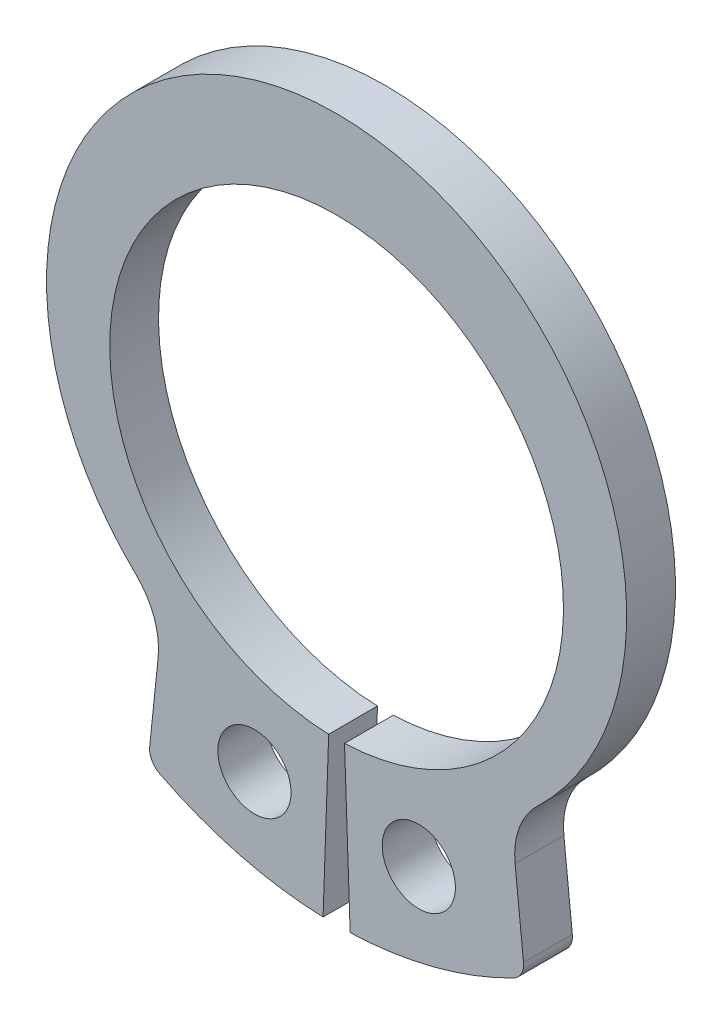
SolidWorks part; units mm, degrees
ref_plane "Front" through (0, 0, 0) normal (0, 0, 1) x (1, 0, 0)
ref_plane "Top" through (0, 0, 0) normal (0, 1, 0) x (1, 0, 0)
ref_plane "Right" through (0, 0, 0) normal (1, 0, 0) x (0, 0, -1)
sketch "Sketch1" plane through (0, 0, 0) normal (0, 0, 1) x (1, 0, 0)
  line L0 (0, 0) -> (-4.027, -2.325) construction
  line L1 (0, 7.95) -> (0, -7.95) construction
  line L2 (-3.8578, -6.9568) -> (-3.5759, -4.2445) construction
  line L4 (-3.5759, -4.2445) -> (-4.1558, -4.9328) construction
  line L5 (-3.5759, -4.2445) -> (0, 0) construction
  line L6 (0, 4.65) -> (0, 6.45) construction
  line L7 (0, 6.45) -> (0, 5.55) construction
  line L8 (0, -4.65) -> (0, -7.95) construction
  line L9 (-2.1265, -7.6653) -> (0, 0) construction
  line L10 (0, 0) -> (-0.2776, -7.95) construction
  line L11 (-3.8578, -6.9568) -> (0, 0) construction
  line L12 (-3.6489, -4.9471) -> (-4.114, -3.7868) construction
  line L13 (-3.8814, -4.3669) -> (-3.5759, -4.2445) construction
  line L14 (-1.243, -4.4808) -> (-2.1265, -7.6653) construction
  line L15 (-1.6848, -6.0731) -> (-0.9621, -6.2736) construction
  arc A0 (0, 6.45) -> (-3.5759, -4.2445) centre (0, 0.5049) ccw construction
  circle A2 centre (0, 0) radius 6.45 construction
  arc A3 (-3.8578, -6.9568) -> (-0.2776, -7.95) centre (0, 0) ccw construction
  circle A4 centre (0, 0) radius 4.65 construction
  circle A6 centre (-1.6848, -6.0731) radius 0.75 construction
  arc A7 (-4.114, -3.7868) -> (-3.6489, -4.9471) centre (-5.1622, -4.8803) cw construction
  point P5 (-4.027, -2.325)
  point P24 (-3.128, -5.6408)
  point P35 (0, 6.45)
  point P36 (0, 4.65)
  point P37 (0, -4.65)
  point P38 (0, -7.95)
  dimension "Ring ID" = 9.3
  dimension "Hole Diameter" = 1.5
  dimension "D10" = 1.5147
  dimension "Max Sec." = 1.8
  dimension "Lug Height" = 3.3
  dimension "D6" = 2
  dimension "D5" = 2.727
  dimension "D8" = 1.25
  dimension "D3" = 120
  dimension "D2" = 3.75
  dimension "D4" = 1.25
sketch "Sketch2" plane through (0, 0, 0) normal (0, 1, 0) x (1, 0, 0)
  line L0 (-6.45, 0.5) -> (-6.45, -0.5) construction
  line L2 (0, 0.5) -> (0, -0.5) construction
  line L4 (-6.45, 0) -> (6.45, 0) construction
  point P3 (-6.45, 0)
  point P6 (0, 0)
  dimension "Ring Thickness" = 1
sketch "Sketch4" plane through (0, 0, 0) normal (0, 0, 1) x (1, 0, 0)
  line L0 (-3.8578, -6.9568) -> (-3.5759, -4.2445) construction
  line L1 (-3.8578, -6.9568) -> (-3.5759, -4.2445)
  line L2 (0, 6.45) -> (0, 4.65)
  line L3 (-0.2776, -7.95) -> (-0.1623, -4.6472)
  line L4 (0, 0) -> (-0.2776, -7.95) construction
  arc A0 (0, 6.45) -> (-3.5759, -4.2445) centre (0, 0.5049) ccw construction
  arc A1 (-3.8578, -6.9568) -> (-0.2776, -7.95) centre (0, 0) ccw construction
  circle A2 centre (-1.6848, -6.0731) radius 0.75 construction
  arc A4 (0, 6.45) -> (-3.5759, -4.2445) centre (0, 0.5049) ccw
  arc A5 (-3.8578, -6.9568) -> (-0.2776, -7.95) centre (0, 0) ccw
  circle A6 centre (-1.6848, -6.0731) radius 0.75
  circle A7 centre (0, 0) radius 4.65 construction
  arc A8 (0, 4.65) -> (-0.1623, -4.6472) centre (0, 0) ccw
extrude "Boss-Extrude1" add sketch "Sketch4" along normal mid plane 1
fillet "Fillet1" radius 1.5147 1 edges at (-3.5759, -4.2445, 0)
fillet "Fillet2" radius 0.3787 1 edges at (-3.8578, -6.9568, 0)
mirror "Mirror1" about plane through (0, 6.45, 0.5) normal (-1, 0, 0) of bodies 109
sketch "Sketch3" plane through (0, 0, 0.5) normal (0, 0, 1) x (1, 0, 0)
  line L0 (3.4625, -3.1038) -> (4.1159, -3.7849) construction
  line L1 (4.1159, -3.7849) -> (4.797, -3.1315) construction
  line L2 (0, 6.45) -> (0, 4.65) construction
  circle A0 centre (0, 0) radius 4.65 construction
  arc A1 (4.1159, -3.7849) -> (-4.1159, -3.7849) centre (0, 0.5049) ccw construction
equation "\"D1@Fillet1\" = \"D10@Sketch1\""
equation "\"D1@Fillet2\" = \"D10@Sketch1\" / 4"
equation "\"Thickness@Boss-Extrude1\"  = \"Ring Thickness@Sketch5\""
equation "\"D2@Sketch1\"=\"Hole Diameter@Sketch1\"*2.5"
equation "\"D4@Sketch1\"=\"D2@Sketch1\"/3"
equation "\"D8@Sketch1\"=\"D4@Sketch1\""
